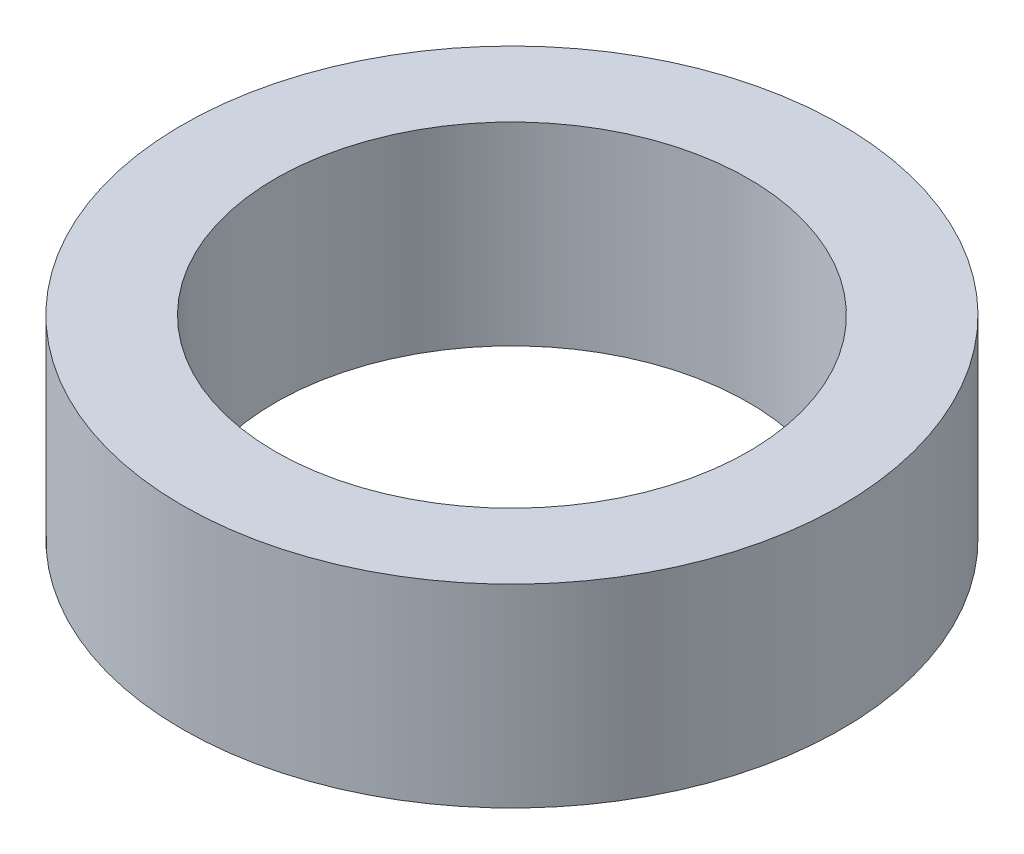
SolidWorks part; units mm, degrees
other "Front Inner Race Locating Sleeve"
ref_plane "Front Plane" through (0, 0, 0) normal (0, 0, 1) x (1, 0, 0)
ref_plane "Top Plane" through (0, 0, 0) normal (0, 1, 0) x (1, 0, 0)
ref_plane "Right Plane" through (0, 0, 0) normal (1, 0, 0) x (0, 0, -1)
sketch3d "Spacer ring sketch datum points"
  point P0 (-56.2917, -149, 0)
  point P1 (-46.2917, -149, 0)
  point P2 (-56.2917, -149, -10)
ref_plane "Spacer ring sketch plane" through (0, -149, 0) normal (0, 1, 0) x (1, 0, 0)
sketch "Spacer ring sketch" plane through (0, -149, 0) normal (0, 1, 0) x (1, 0, 0)
  circle A0 centre (-56.2917, 0) radius 8.5
  circle A1 centre (-56.2917, 0) radius 6.1
extrude "Spacer ring" add sketch "Spacer ring sketch" along normal blind 5 separate body
